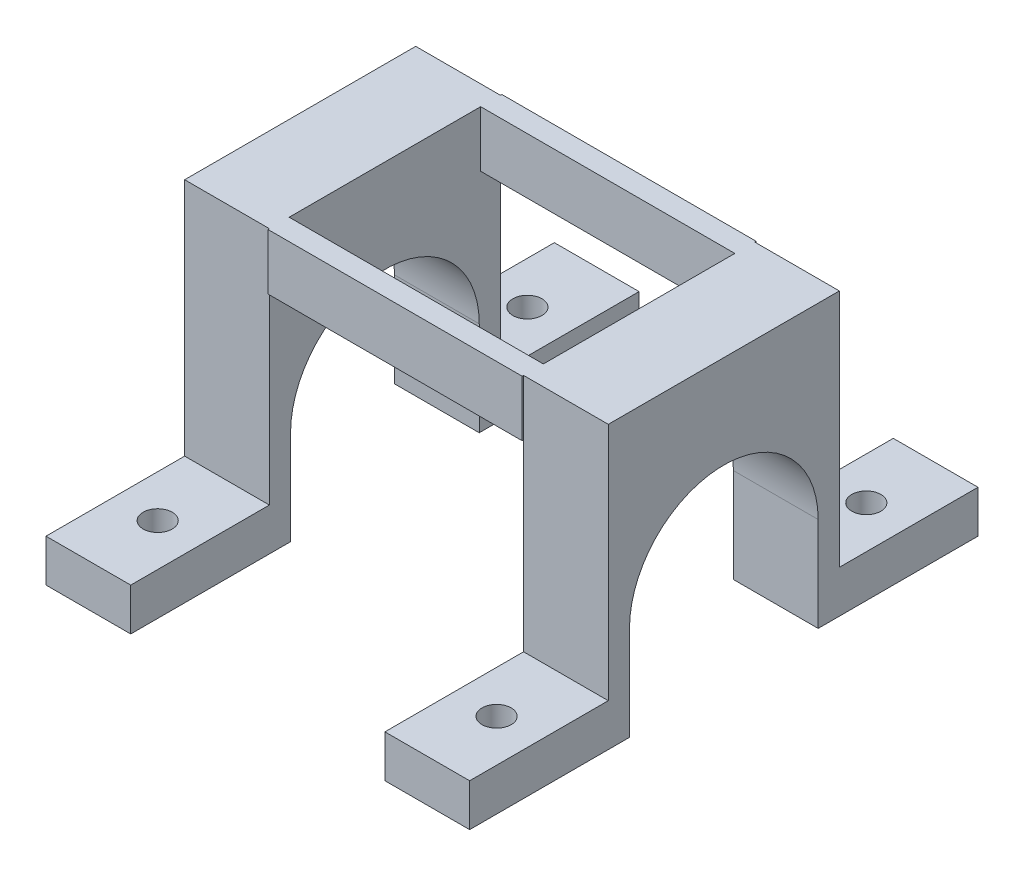
SolidWorks part; units mm, degrees
ref_plane "Front Plane" through (0, 0, 0) normal (0, 0, 1) x (1, 0, 0)
ref_plane "Top Plane" through (0, 0, 0) normal (0, 1, 0) x (1, 0, 0)
ref_plane "Right Plane" through (0, 0, 0) normal (1, 0, 0) x (0, 0, -1)
sketch "Sketch1" plane through (0, 0, 0) normal (1, 0, 0) x (0, 0, -1)
  line L0 (28.2951, 2.3542) -> (52.2537, 2.3542)
  line L1 (52.2537, 2.3542) -> (52.2537, 8.7042)
  line L2 (52.2537, 8.7042) -> (31.4701, 8.7042)
  line L3 (31.4701, 8.7042) -> (31.4701, 16.4957)
  line L4 (0.0122, 2.3542) -> (-23.9463, 2.3542)
  line L5 (-23.9463, 2.3542) -> (-23.9463, 8.7042)
  line L6 (-23.9463, 8.7042) -> (-3.1628, 8.7042)
  line L7 (-3.1628, 8.7042) -> (-3.1628, 16.4957)
  line L8 (0.0122, 16.4957) -> (0.0122, 2.3542)
  line L9 (28.2951, 16.4957) -> (28.2951, 2.3542)
  arc A0 (28.2951, 16.4957) -> (0.0122, 16.4957) centre (14.1537, 16.4957) ccw
  arc A1 (31.4701, 16.4957) -> (-3.1628, 16.4957) centre (14.1537, 16.4957) ccw
  circle A2 centre (14.1537, 16.4957) radius 17.3164 construction
  circle A3 centre (14.1537, 16.4957) radius 14.1415 construction
  dimension "D2" = 28.2829
  dimension "D4" = 6.35
  dimension "D6" = 6.35
  dimension "D1" = 3.175
extrude "Boss-Extrude1" add sketch "Sketch1" along normal blind 12.7
ref_plane "Plane1" through (0, 44.5817, 0) normal (0, 1, 0) x (1, 0, 0)
ref_plane "Plane2" through (12.7, 8.7042, -31.4701) normal (-1, 0, 0) x (0, 0, 1)
sketch "Sketch4" plane through (0, 44.5817, 0) normal (0, 1, 0) x (1, 0, 0)
  line L0 (12.7, 34.9626) -> (12.7, 27.9776) construction
  line L1 (0, -3.1628) -> (12.7, -3.1628)
  line L2 (0, -3.1628) -> (0, 31.4701)
  line L3 (0, 31.4701) -> (12.7, 31.4701)
  line L4 (12.7, -3.1628) -> (12.7, 31.4701)
  line L5 (12.7, 31.4701) -> (0, 31.4701) construction
extrude "Boss-Extrude2" add sketch "Sketch4" against normal up to surface (28.086 mm away)
sketch "Sketch6" plane through (12.7, 0, 0) normal (1, 0, 0) x (0, 0, -1)
  line L0 (-3.1628, 44.5817) -> (31.4701, 44.5817) construction
  line L1 (-3.3723, 44.5817) -> (-0.1973, 44.5817)
  line L2 (-3.3723, 44.5817) -> (-3.3723, 36.1997)
  line L3 (-3.3723, 36.1997) -> (-0.1973, 36.1997)
  line L4 (-0.1973, 44.5817) -> (-0.1973, 36.1997)
  line L5 (-3.1628, 44.5817) -> (-3.1628, 8.7042) construction
  line L6 (31.6797, 44.5817) -> (28.5047, 44.5817)
  line L7 (31.6797, 44.5817) -> (31.6797, 36.1997)
  line L8 (31.6797, 36.1997) -> (28.5047, 36.1997)
  line L9 (28.5047, 44.5817) -> (28.5047, 36.1997)
  line L10 (31.4701, 8.7042) -> (31.4701, 44.5817) construction
  line L11 (-3.3723, 44.5817) -> (-0.1973, 44.5817)
  line L12 (31.6797, 44.5817) -> (28.5047, 44.5817)
  dimension "D1" = 3.175
  dimension "D2" = 3.175
  dimension "D3" = 0.2095
  dimension "D4" = 0.2095
  dimension "D5" = 8.382
  dimension "D6" = 8.382
extrude "Boss-Extrude3" add sketch "Sketch6" along normal blind 19.05 contours L2 L1 L4 L3 | L7 L6 L9 L8
sketch "Sketch7" plane through (0, 8.7042, 0) normal (0, 1, 0) x (1, 0, 0)
  line L0 (12.7, -3.1628) -> (0, -3.1628) construction
  line L1 (0, -3.1628) -> (0, -23.9463) construction
  line L2 (12.7, -3.1628) -> (12.7, -23.9463) construction
  line L3 (12.7, -23.9463) -> (0, -23.9463) construction
  line L4 (12.7, 52.2537) -> (0, 52.2537) construction
  line L5 (0, 52.2537) -> (0, 31.4701) construction
  circle A0 centre (6.35, 41.8619) radius 2.1828
  circle A1 centre (6.35, -13.5545) radius 2.1828
  dimension "D1" = 4.3656
  dimension "D2" = 4.3656
  dimension "D3" = 6.35
  dimension "D4" = 12.7
  dimension "D5" = 20.7836
  dimension "D6" = 10.3918
  dimension "D7" = 10.3918
  dimension "D8" = 6.35
extrude "Cut-Extrude1" cut sketch "Sketch7" against normal blind 12.7
ref_plane "Plane3" through (31.75, 0, 0) normal (1, 0, 0) x (0, 0, -1)
mirror "Mirror1" about plane through (31.75, 0, 0) normal (1, 0, 0) of bodies 104
